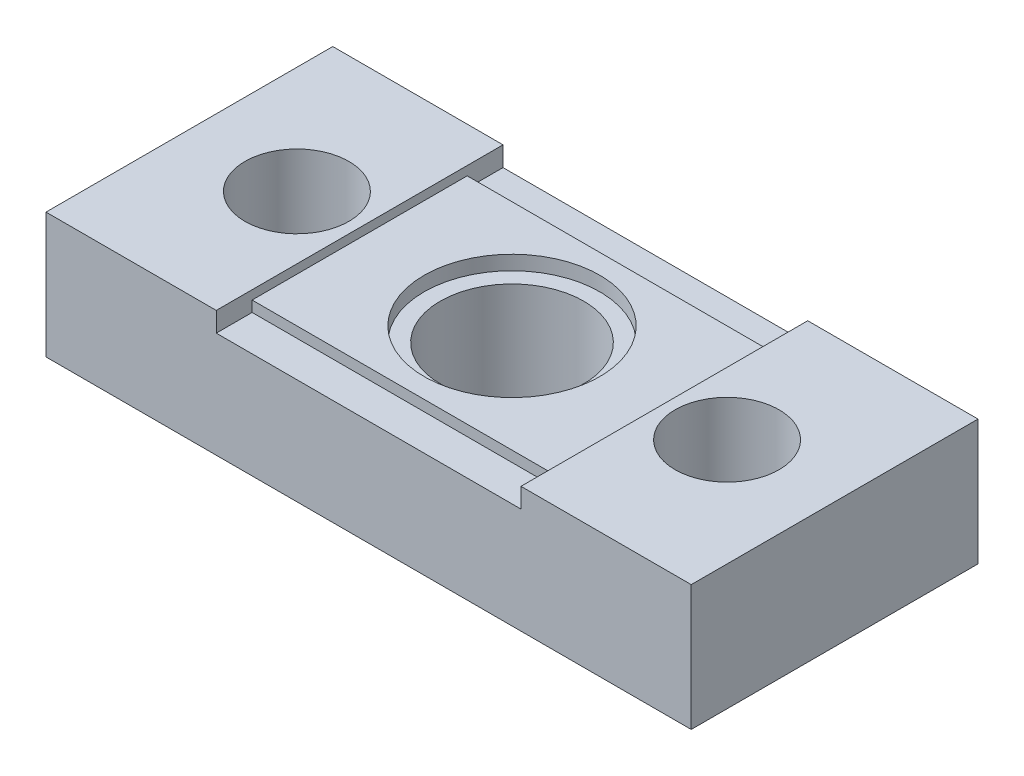
SolidWorks part; units mm, degrees
ref_plane "Front" through (0, 0, 0) normal (0, 0, 1) x (1, 0, 0)
ref_plane "Top" through (0, 0, 0) normal (0, 1, 0) x (1, 0, 0)
ref_plane "Right" through (0, 0, 0) normal (1, 0, 0) x (0, 0, -1)
sketch "草图1" plane through (0, 0, 0) normal (0, 1, 0) x (1, 0, 0)
  line L1 (-18, -8) -> (18, -8)
  line L2 (-18, -8) -> (-18, 8)
  line L3 (-18, 8) -> (18, 8)
  line L4 (18, -8) -> (18, 8)
  line L5 (-18, -8) -> (18, 8) construction
  line L6 (-18, 8) -> (18, -8) construction
  point P0 (0, 0)
  dimension "D1" = 16
  dimension "D2" = 36
extrude "凸台-拉伸1" add sketch "草图1" along normal blind 7
sketch "草图4" plane through (0, 0, -8) normal (0, 0, -1) x (-1, 0, 0)
  line L0 (0, 9.3481) -> (0, -3.6529) construction
  line L1 (-8.5, 7) -> (-8.5, 6.5)
  line L2 (-18, 7) -> (18, 7) construction
  line L3 (-8.5, 6.5) -> (8.5, 6.5)
  line L4 (8.5, 6.5) -> (8.5, 7)
  dimension "D1" = 17
  dimension "D2" = 0.5
extrude "切除-拉伸1" cut sketch "草图4" against normal through all and the other way through all
sketch "草图5" plane through (0, 6.5, 0) normal (0, 1, 0) x (1, 0, 0)
  circle A0 centre (0, 0) radius 4.9
  dimension "D1" = 9.8
extrude "切除-拉伸2" cut sketch "草图5" against normal blind 0.8
sketch "草图6" plane through (0, 5.7, 0) normal (0, 1, 0) x (1, 0, 0)
  circle A0 centre (0, 0) radius 4
  dimension "D1" = 8
extrude "切除-拉伸3" cut sketch "草图6" against normal through all
sketch "草图7" plane through (0, 6.5, 0) normal (0, 1, 0) x (1, 0, 0)
  line L0 (8.5, 8) -> (8.5, -8) construction
  line L1 (-8.5, 8) -> (8.5, 8)
  line L2 (-8.5, 8) -> (-8.5, 6)
  line L3 (-8.5, 6) -> (8.5, 6)
  line L4 (8.5, 8) -> (8.5, 6)
  dimension "D1" = 17
  dimension "D2" = 2
extrude "切除-拉伸4" cut sketch "草图7" against normal blind 0.6
sketch "草图8" plane through (0, 6.5, 0) normal (0, 1, 0) x (1, 0, 0)
  line L0 (-8.5, 6) -> (-8.5, -8) construction
  line L1 (8.5, -8) -> (-8.5, -8)
  line L2 (8.5, -8) -> (8.5, -6)
  line L3 (8.5, -6) -> (-8.5, -6)
  line L4 (-8.5, -8) -> (-8.5, -6)
  dimension "D1" = 17
  dimension "D2" = 2
extrude "切除-拉伸5" cut sketch "草图8" against normal blind 0.6
sketch "草图9" plane through (0, 7, 0) normal (0, 1, 0) x (1, 0, 0)
  line L0 (-18, 8) -> (-18, -8) construction
  line L2 (-8.5, 8) -> (-18, 8) construction
  circle A0 centre (-12, 0) radius 2.9
  circle A1 centre (12, 0) radius 2.9
  point P6 (-18, 0)
  dimension "D1" = 5.8
  dimension "D2" = 5.8
  dimension "D3" = 6
  dimension "D5" = 8
extrude "切除-拉伸6" cut sketch "草图9" against normal through all
